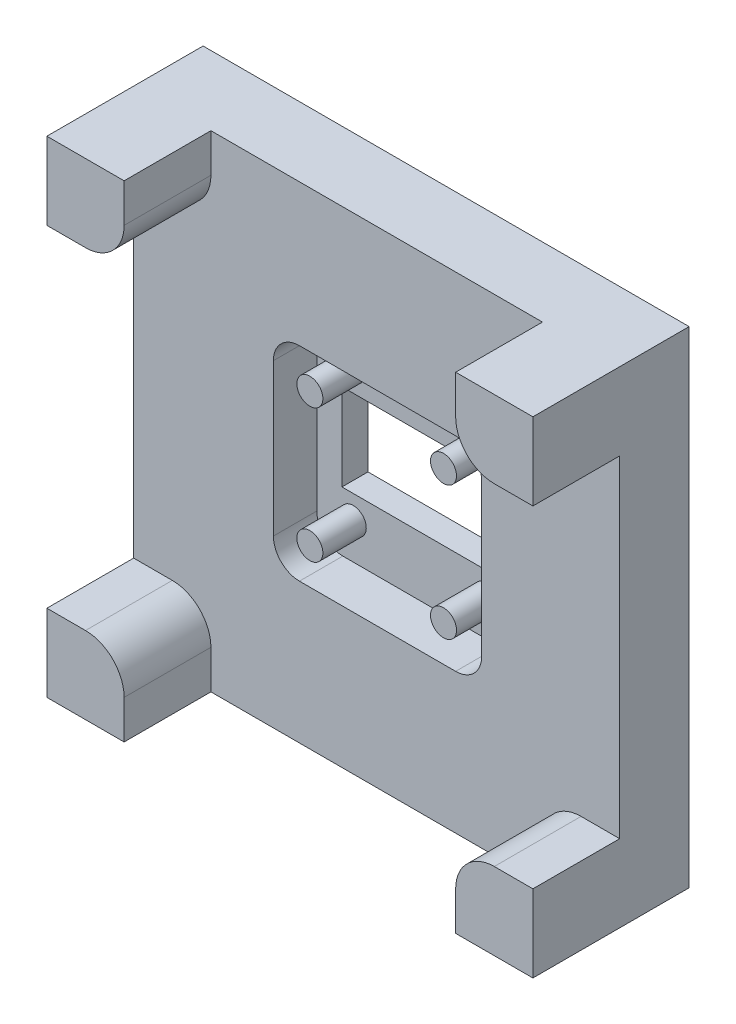
SolidWorks part; units mm, degrees
ref_plane "Plano frontal" through (0, 0, 0) normal (0, 0, 1) x (1, 0, 0)
ref_plane "Plano superior" through (0, 0, 0) normal (0, 1, 0) x (1, 0, 0)
ref_plane "Plano direito" through (0, 0, 0) normal (1, 0, 0) x (0, 0, -1)
sketch "Esboço1" plane through (0, 0, 0) normal (0, 0, 1) x (1, 0, 0)
  line L1 (28, -28) -> (-28, -28)
  line L2 (28, -28) -> (28, 28)
  line L3 (28, 28) -> (-28, 28)
  line L4 (-28, -28) -> (-28, 28)
  line L5 (28, -28) -> (-28, 28) construction
  line L6 (28, 28) -> (-28, -28) construction
  point P0 (0, 0)
  dimension "D1" = 56
extrude "Ressalto-extrusão1" add sketch "Esboço1" along normal blind 8
sketch "Esboço2" plane through (0, 0, 8) normal (0, 0, 1) x (1, 0, 0)
  line L0 (-19.1, 23.55) -> (-19.1, 28)
  line L1 (-23.55, 19.1) -> (-28, 19.1)
  line L2 (-28, 19.1) -> (-28, 28)
  line L3 (-28, 28) -> (-19.1, 28)
  line L4 (28, 28) -> (-28, 28) construction
  line L7 (-28, 28) -> (-28, -28) construction
  arc A1 (-19.1, 23.55) -> (-23.55, 19.1) centre (-23.55, 23.55) cw
  dimension "D1" = 4.45
  dimension "D2" = 4.45
  dimension "D3" = 4.45
extrude "Ressalto-extrusão2" add sketch "Esboço2" along normal blind 10
mirror "Espelhar1" about plane through (0, 0, 0) normal (1, 0, 0) of "Ressalto-extrusão2"
mirror "Espelhar2" about plane through (0, 0, 0) normal (0, 1, 0) of "Espelhar1", "Ressalto-extrusão2"
sketch "Esboço3" plane through (0, 0, 8) normal (0, 0, 1) x (1, 0, 0)
  line L0 (9.1, -11.85) -> (-8.9, -11.85)
  line L1 (12.1, -8.85) -> (12.1, 8.65)
  line L2 (9.1, 11.65) -> (-8.9, 11.65)
  line L3 (-11.9, -8.85) -> (-11.9, 8.65)
  line L4 (7.7, 6.2) -> (7.7, -6.2) construction
  line L9 (-6.2, 7.7) -> (6.2, 7.7) construction
  line L10 (6.2, -7.7) -> (-6.2, -7.7) construction
  line L11 (-7.7, 6.2) -> (-7.7, -6.2) construction
  arc A0 (-8.9, 11.65) -> (-11.9, 8.65) centre (-8.9, 8.65) ccw
  arc A1 (-8.9, -11.85) -> (-11.9, -8.85) centre (-8.9, -8.85) cw
  arc A2 (9.1, -11.85) -> (12.1, -8.85) centre (9.1, -8.85) ccw
  arc A3 (12.1, 8.65) -> (9.1, 11.65) centre (9.1, 8.65) ccw
  circle A8 centre (-7.7, 7.7) radius 1.5
  circle A9 centre (7.7, 7.7) radius 1.5
  circle A10 centre (7.7, -7.7) radius 1.5
  circle A11 centre (-7.7, -7.7) radius 1.5
  point P0 (0, 0)
  point P30 (0, 7.7)
  point P31 (-7.7, 0)
  dimension "D3" = 3
  dimension "D4" = 3
  dimension "D5" = 3
  dimension "D6" = 11.85
  dimension "D8" = 12.4
  dimension "D1" = 23.5
  dimension "D2" = 24
  dimension "D7" = 12.1
  dimension "D9" = 12.4
extrude "Corte-extrusão1" cut sketch "Esboço3" against normal blind 5
sketch "Esboço4" plane through (0, 0, 3) normal (0, 0, 1) x (1, 0, 0)
  line L1 (9, -5) -> (-9, -5)
  line L2 (9, -5) -> (9, 5)
  line L3 (9, 5) -> (-9, 5)
  line L4 (-9, -5) -> (-9, 5)
  line L5 (9, -5) -> (-9, 5) construction
  line L6 (9, 5) -> (-9, -5) construction
  point P0 (0, 0)
  dimension "D1" = 18
  dimension "D2" = 10
extrude "Corte-extrusão2" cut sketch "Esboço4" against normal blind 12
